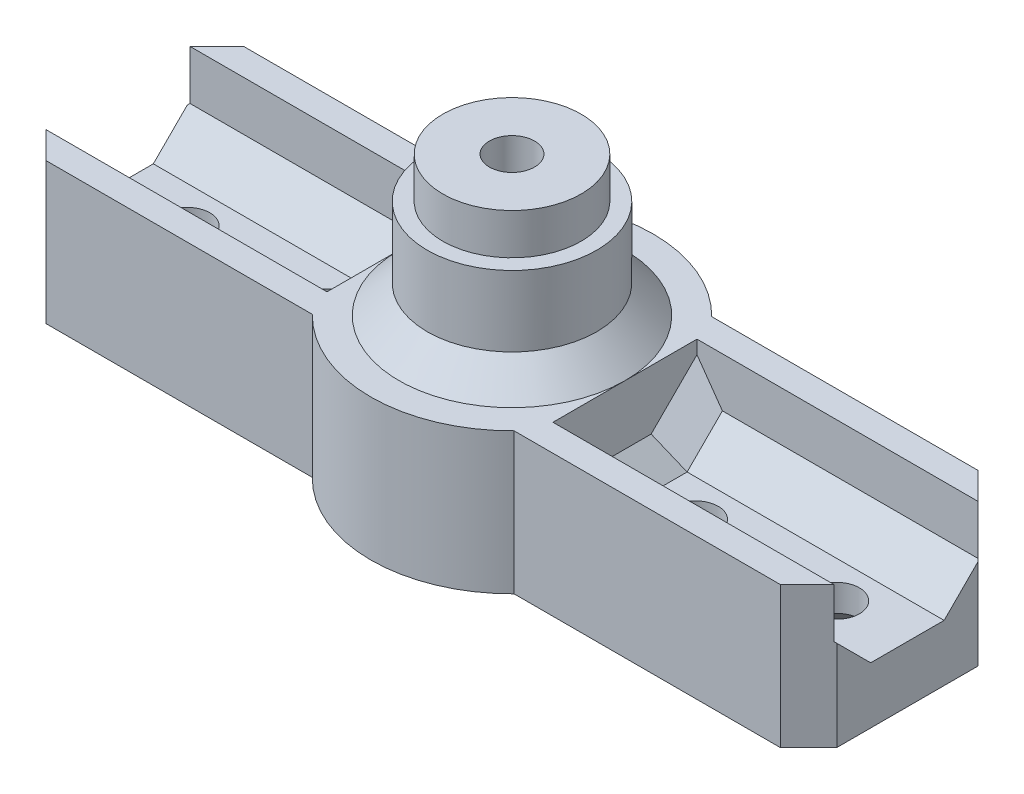
SolidWorks part; units mm, degrees
ref_plane "Plan de face" through (0, 0, 0) normal (0, 0, 1) x (1, 0, 0)
ref_plane "Plan de dessus" through (0, 0, 0) normal (0, 1, 0) x (1, 0, 0)
ref_plane "Plan de droite" through (0, 0, 0) normal (1, 0, 0) x (0, 0, -1)
sketch "Esquisse1" plane through (0, 0, 0) normal (0, 1, 0) x (1, 0, 0)
  line L0 (7.1414, 7) -> (28, 7)
  line L1 (-28, -7) -> (-7.1414, -7)
  line L2 (-28, -7) -> (-28, 7)
  line L3 (-28, 7) -> (-7.1414, 7)
  line L4 (28, -7) -> (28, 7)
  line L5 (-28, -7) -> (28, 7) construction
  line L6 (-28, 7) -> (28, -7) construction
  line L7 (7.1414, -7) -> (28, -7)
  arc A0 (-7.1414, -7) -> (7.1414, -7) centre (0, 0) ccw
  arc A1 (7.1414, 7) -> (-7.1414, 7) centre (0, 0) ccw
  dimension "D1" = 20
  dimension "D2" = 14
  dimension "D3" = 56
extrude "Boss.-Extru.1" add sketch "Esquisse1" along normal blind 10
sketch "Esquisse2" plane through (-28, 0, 0) normal (-1, 0, 0) x (0, 0, 1)
  line L0 (-7, 10) -> (7, 10) construction
  line L1 (-5.1, 10) -> (5.1, 10)
  line L2 (-5.1, 10) -> (-5.1, 4)
  line L3 (-5.1, 4) -> (5.1, 4)
  line L4 (5.1, 10) -> (5.1, 4)
  line L5 (-7, 0) -> (7, 0) construction
  point P6 (0, 0)
  dimension "D1" = 6
  dimension "D2" = 10.2
  dimension "D3" = 5.1
extrude "Enlèv. mat.-Extru.1" cut sketch "Esquisse2" against normal blind 20
chamfer "Chanfrein1" distance 2.5 angle 45 2 edges at (-18, 4, 5.1) (-18, 4, -5.1)
chamfer "Chanfrein2" distance 1.8 angle 45 3 edges at (-8, 5.25, 3.85) (-8, 4, 0) (-8, 5.25, -3.85)
mirror "Symétrie1" about plane through (0, 0, 0) normal (1, 0, 0) of "Chanfrein2", "Chanfrein1", "Enlèv. mat.-Extru.1"
sketch "Esquisse5" plane through (0, 0, 0) normal (0, -1, 0) x (1, 0, 0)
  line L0 (-32.8926, 0) -> (36.0103, 0) construction
  line L1 (28, 7) -> (28, -7) construction
  line L2 (-28, -7) -> (-28, 7) construction
  circle A0 centre (-23, 0) radius 1.6
  circle A1 centre (-13, 0) radius 1.6
  circle A2 centre (13, 0) radius 1.6
  circle A3 centre (23, 0) radius 1.6
  dimension "D1" = 3.2
  dimension "D2" = 3.2
  dimension "D3" = 3.2
  dimension "D4" = 3.2
  dimension "D5" = 5
  dimension "D6" = 10
  dimension "D7" = 10
  dimension "D8" = 5
extrude "Enlèv. mat.-Extru.4" cut sketch "Esquisse5" against normal blind 7
chamfer "Chanfrein4" distance 2.1 angle 45 4 edges at (23, 0, -1.6) (13, 0, -1.6) (-23, 0, -1.6) (-13, 0, -1.6)
chamfer "Chanfrein5" distance 2 angle 45 4 edges at (28, 5, -7) (28, 5, 7) (-28, 5, -7) (-28, 5, 7)
sketch "Esquisse6" plane through (0, 10, 0) normal (0, 1, 0) x (1, 0, 0)
  circle A0 centre (0, 0) radius 6
  dimension "D1" = 12
extrude "Boss.-Extru.2" add sketch "Esquisse6" along normal blind 7
sketch "Esquisse7" plane through (0, 17, 0) normal (0, 1, 0) x (1, 0, 0)
  circle A0 centre (0, 0) radius 4.9
  dimension "D1" = 9.8
extrude "Boss.-Extru.3" add sketch "Esquisse7" along normal blind 2.9
sketch "Esquisse8" plane through (0, 19.9, 0) normal (0, 1, 0) x (1, 0, 0)
  circle A0 centre (0, 0) radius 1.6
  dimension "D1" = 3.2
extrude "Enlèv. mat.-Extru.5" cut sketch "Esquisse8" against normal through all
chamfer "Chanfrein6" distance 2.1 angle 45 1 edges at (0, 0, 1.6)
chamfer "Chanfrein7" distance 2 angle 45 1 edges at (0, 10, 6)
